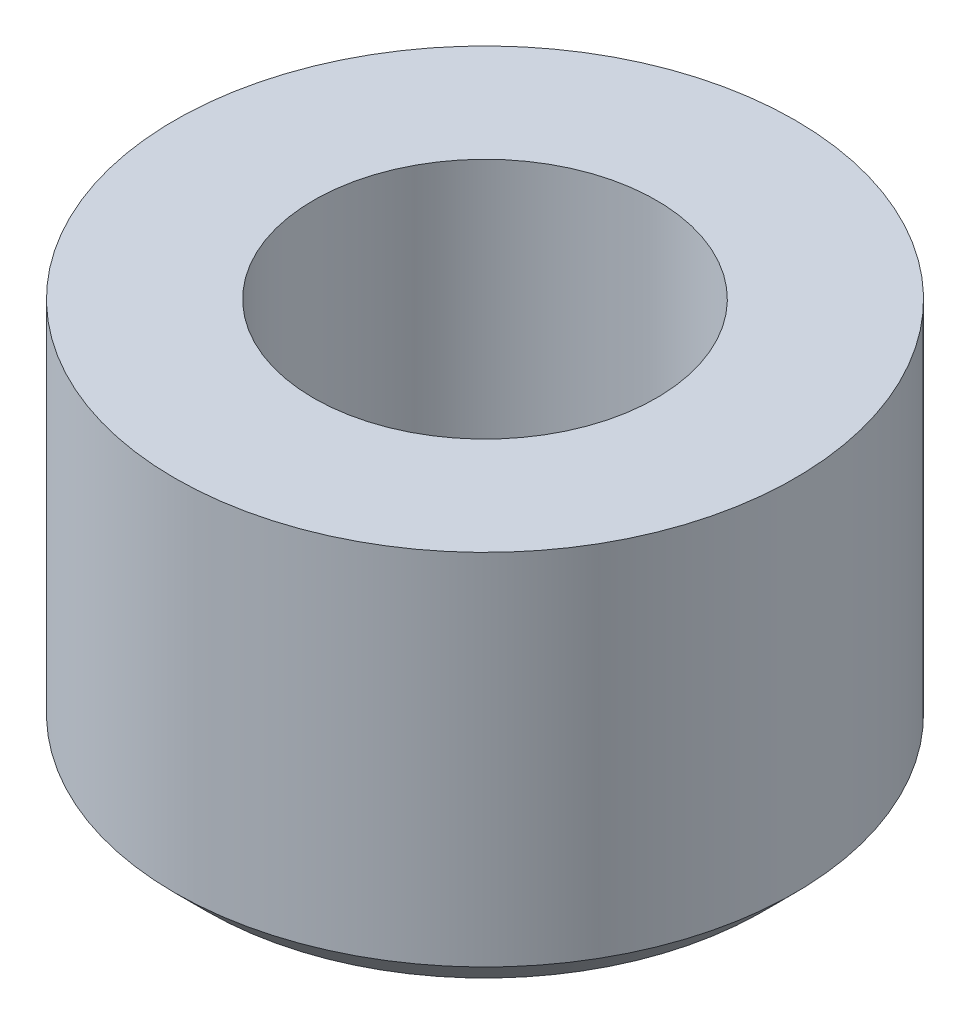
SolidWorks part; units mm, degrees
ref_plane "Front Plane" through (0, 0, 0) normal (0, 0, 1) x (1, 0, 0)
ref_plane "Top Plane" through (0, 0, 0) normal (0, 1, 0) x (1, 0, 0)
ref_plane "Right Plane" through (0, 0, 0) normal (1, 0, 0) x (0, 0, -1)
sketch "Sketch1" plane through (0, 0, 0) normal (0, 1, 0) x (1, 0, 0)
  circle A0 centre (0, 0) radius 3.8
  circle A1 centre (0, 0) radius 2.1
  dimension "D1" = 7.6
  dimension "D2" = 4.2
extrude "Boss-Extrude1" add sketch "Sketch1" along normal blind 4.8
chamfer "Chamfer1" distance 0.4 angle 45 1 edges at (0, 0, 3.8)
